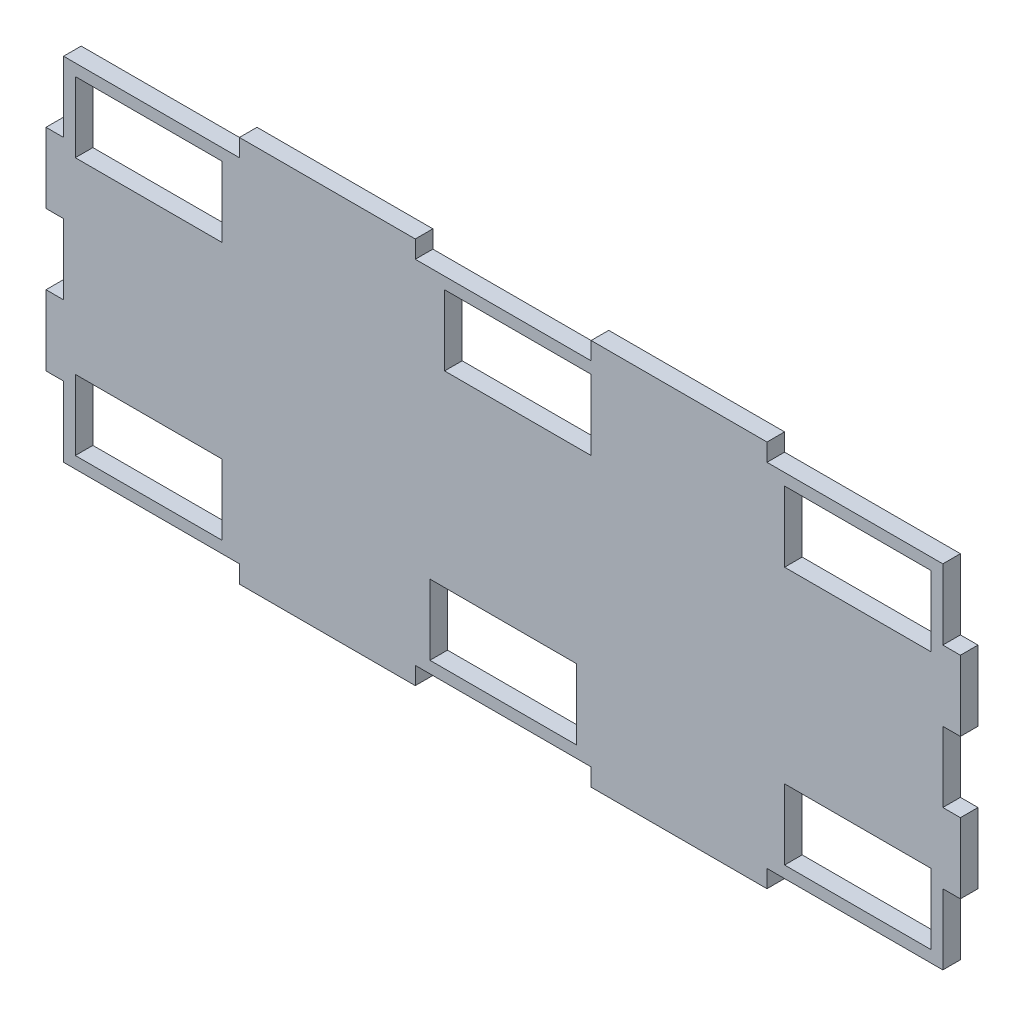
SolidWorks part; units mm, degrees
material "Pinho"
ref_plane "Plano frontal" through (0, 0, 0) normal (0, 0, 1) x (1, 0, 0)
ref_plane "Plano superior" through (0, 0, 0) normal (0, 1, 0) x (1, 0, 0)
ref_plane "Plano direito" through (0, 0, 0) normal (1, 0, 0) x (0, 0, -1)
sketch "Esboço1" plane through (0, 0, 0) normal (0, 0, 1) x (1, 0, 0)
  line L0 (-15, 30) -> (15, 30)
  line L1 (-75, -30) -> (-45, -30)
  line L2 (-75, -30) -> (-75, -18)
  line L3 (-75, 30) -> (-45, 30)
  line L4 (75, -30) -> (75, -18)
  line L5 (-75, -30) -> (75, 30) construction
  line L6 (-75, 30) -> (75, -30) construction
  line L8 (-45, 30) -> (-45, 33)
  line L9 (-45, 33) -> (-15, 33)
  line L10 (-15, 30) -> (-15, 33)
  line L11 (-15, -30) -> (15, -30)
  line L14 (15, 30) -> (15, 33)
  line L15 (15, 33) -> (45, 33)
  line L16 (45, 30) -> (45, 33)
  line L17 (-45, -30) -> (-45, -33)
  line L18 (-45, -33) -> (-15, -33)
  line L19 (45, 30) -> (75, 30)
  line L20 (-15, -30) -> (-15, -33)
  line L21 (45, -30) -> (75, -30)
  line L22 (75, 18) -> (75, 30)
  line L24 (15, -30) -> (15, -33)
  line L25 (15, -33) -> (45, -33)
  line L26 (45, -30) -> (45, -33)
  line L27 (-75, 18) -> (-78, 18)
  line L29 (-75, 6) -> (-78, 6)
  line L30 (-78, 18) -> (-78, 6)
  line L32 (73, -16) -> (48, -16)
  line L33 (-75, -6) -> (-78, -6)
  line L35 (-75, -18) -> (-78, -18)
  line L36 (-78, -6) -> (-78, -18)
  line L37 (-75, 18) -> (-75, 30)
  line L38 (73, -16) -> (73, -28)
  line L39 (75, 6) -> (78, 6)
  line L41 (75, 18) -> (78, 18)
  line L42 (78, 6) -> (78, 18)
  line L43 (75, -6) -> (75, 6)
  line L44 (-75, -6) -> (-75, 6)
  line L45 (75, -18) -> (78, -18)
  line L47 (75, -6) -> (78, -6)
  line L48 (78, -18) -> (78, -6)
  line L49 (73, -28) -> (48, -28)
  line L50 (48, -16) -> (48, -28)
  line L51 (73, -16) -> (48, -28) construction
  line L52 (73, -28) -> (48, -16) construction
  line L53 (-73, -16) -> (-48, -16)
  line L54 (-73, -16) -> (-73, -28)
  line L55 (-73, -28) -> (-48, -28)
  line L56 (-48, -16) -> (-48, -28)
  line L57 (-73, -16) -> (-48, -28) construction
  line L58 (-73, -28) -> (-48, -16) construction
  line L59 (-73, 16) -> (-48, 16)
  line L60 (-73, 16) -> (-73, 28)
  line L61 (-73, 28) -> (-48, 28)
  line L62 (-48, 16) -> (-48, 28)
  line L63 (-73, 16) -> (-48, 28) construction
  line L64 (-73, 28) -> (-48, 16) construction
  line L65 (73, 28) -> (48, 28)
  line L66 (73, 28) -> (73, 16)
  line L67 (73, 16) -> (48, 16)
  line L68 (48, 28) -> (48, 16)
  line L69 (73, 28) -> (48, 16) construction
  line L70 (73, 16) -> (48, 28) construction
  line L71 (12.5, -28) -> (-12.5, -28)
  line L72 (12.5, -28) -> (12.5, -16)
  line L73 (12.5, -16) -> (-12.5, -16)
  line L74 (-12.5, -28) -> (-12.5, -16)
  line L75 (12.5, -28) -> (-12.5, -16) construction
  line L76 (12.5, -16) -> (-12.5, -28) construction
  line L77 (15, 16) -> (-10, 16)
  line L78 (15, 16) -> (15, 28)
  line L79 (15, 28) -> (-10, 28)
  line L80 (-10, 16) -> (-10, 28)
  line L81 (15, 16) -> (-10, 28) construction
  line L82 (15, 28) -> (-10, 16) construction
  point P0 (0, 0)
  point P6 (-60.5, -22)
  point P32 (60.5, -22)
  point P48 (-60.5, 22)
  point P53 (60.5, 22)
  point P58 (2.5, 22)
  point P59 (0, -22)
  dimension "D1" = 150
  dimension "D2" = 60
  dimension "D3" = 30
  dimension "D4" = 30
  dimension "D5" = 30
  dimension "D6" = 30
  dimension "D7" = 3
  dimension "D8" = 3
  dimension "D9" = 30
  dimension "D10" = 30
  dimension "D11" = 30
  dimension "D12" = 30
  dimension "D13" = 3
  dimension "D14" = 3
  dimension "D15" = 12
  dimension "D16" = 12
  dimension "D17" = 12
  dimension "D18" = 12
  dimension "D19" = 12
  dimension "D20" = 12
  dimension "D21" = 12
  dimension "D22" = 12
  dimension "D23" = 3
  dimension "D24" = 3
  dimension "D25" = 3
  dimension "D26" = 3
  dimension "D27" = 12
  dimension "D28" = 25
  dimension "D29" = 25
  dimension "D30" = 12
  dimension "D31" = 25
  dimension "D32" = 12
  dimension "D33" = 25
  dimension "D34" = 12
  dimension "D35" = 2
  dimension "D36" = 2
  dimension "D37" = 2
  dimension "D38" = 2
  dimension "D39" = 2
  dimension "D40" = 2
  dimension "D41" = 2
  dimension "D42" = 2
  dimension "D43" = 12
  dimension "D44" = 25
  dimension "D45" = 25
  dimension "D46" = 12
  dimension "D47" = 2.5
  dimension "D48" = 5
  dimension "D49" = 2
  dimension "D50" = 2
extrude "Ressalto-extrusão1" add sketch "Esboço1" along normal blind 3
